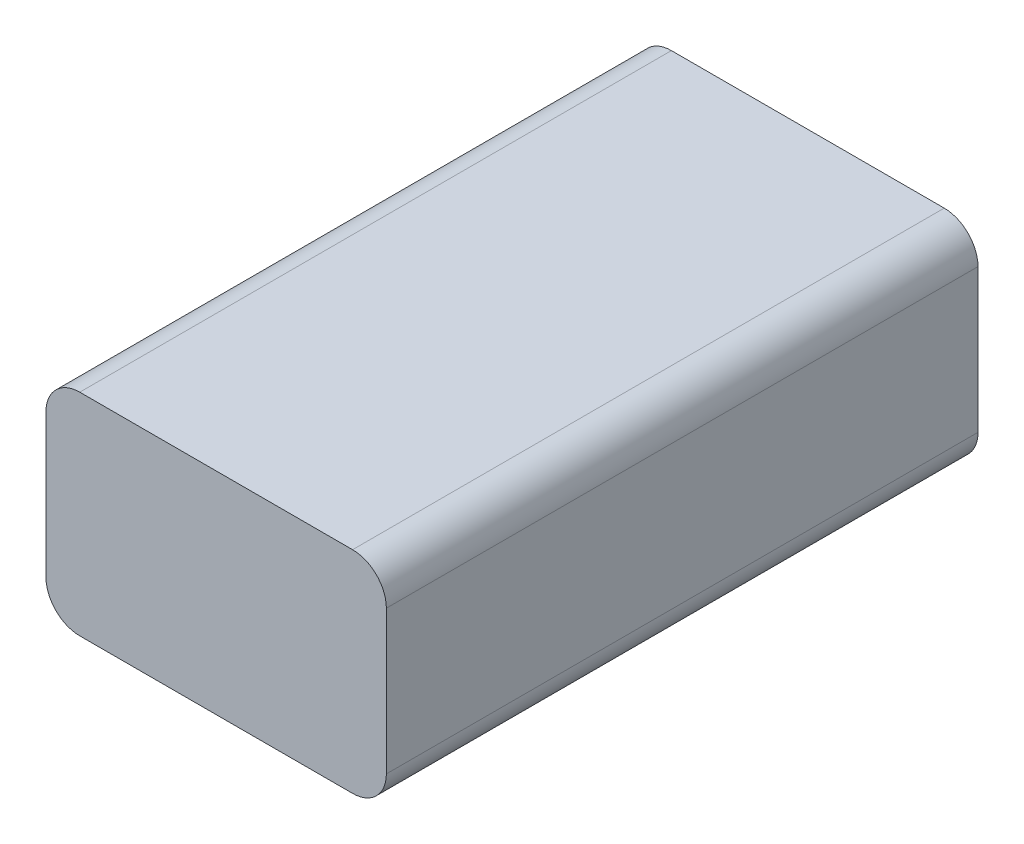
SolidWorks part; units mm, degrees
ref_plane "Front Plane" through (0, 0, 0) normal (0, 0, 1) x (1, 0, 0)
ref_plane "Top Plane" through (0, 0, 0) normal (0, 1, 0) x (1, 0, 0)
ref_plane "Right Plane" through (0, 0, 0) normal (1, 0, 0) x (0, 0, -1)
sketch "Sketch1" plane through (0, 0, 0) normal (0, 1, 0) x (1, 0, 0)
  line L1 (0, 0) -> (25.6, 0)
  line L2 (0, 0) -> (0, 44.5)
  line L3 (0, 44.5) -> (25.6, 44.5)
  line L4 (25.6, 0) -> (25.6, 44.5)
  dimension "D1" = 44.5
  dimension "D2" = 25.6
extrude "Boss-Extrude1" add sketch "Sketch1" along normal blind 15.875
sketch "Sketch2" plane through (0, 0, -44.5) normal (0, 0, -1) x (-1, 0, 0)
  line L1 (-19.4902, 3.1274) -> (-14.4901, 4.0871)
  line L2 (-14.4901, 4.0871) -> (-12.8212, 8.8972)
  line L3 (-12.8212, 8.8972) -> (-16.1524, 12.7476)
  line L4 (-16.1524, 12.7476) -> (-21.1525, 11.7879)
  line L5 (-21.1525, 11.7879) -> (-22.8214, 6.9778)
  line L6 (-22.8214, 6.9778) -> (-19.4902, 3.1274)
  line L7 (-19.2527, 3.767) -> (-14.9253, 4.6127)
  line L8 (-14.9253, 4.6127) -> (-13.4939, 8.7831)
  line L9 (-13.4939, 8.7831) -> (-16.39, 12.108)
  line L10 (-16.39, 12.108) -> (-20.7174, 11.2623)
  line L11 (-20.7174, 11.2623) -> (-22.1487, 7.0919)
  line L12 (-22.1487, 7.0919) -> (-19.2527, 3.767)
  circle A0 centre (-6.0692, 7.9375) radius 3.1085
  circle A1 centre (-17.8213, 7.9375) radius 4.4093 construction
  circle A2 centre (-6.0692, 7.9375) radius 2.6156
  circle A3 centre (-17.8213, 7.9375) radius 3.8185 construction
extrude "Boss-Extrude2" add sketch "Sketch2" along normal blind 2
fillet "Fillet1" radius 2.54 4 edges at (25.6, 0, -22.25) (0, 0, -22.25) (0, 15.875, -22.25) (25.6, 15.875, -22.25)
